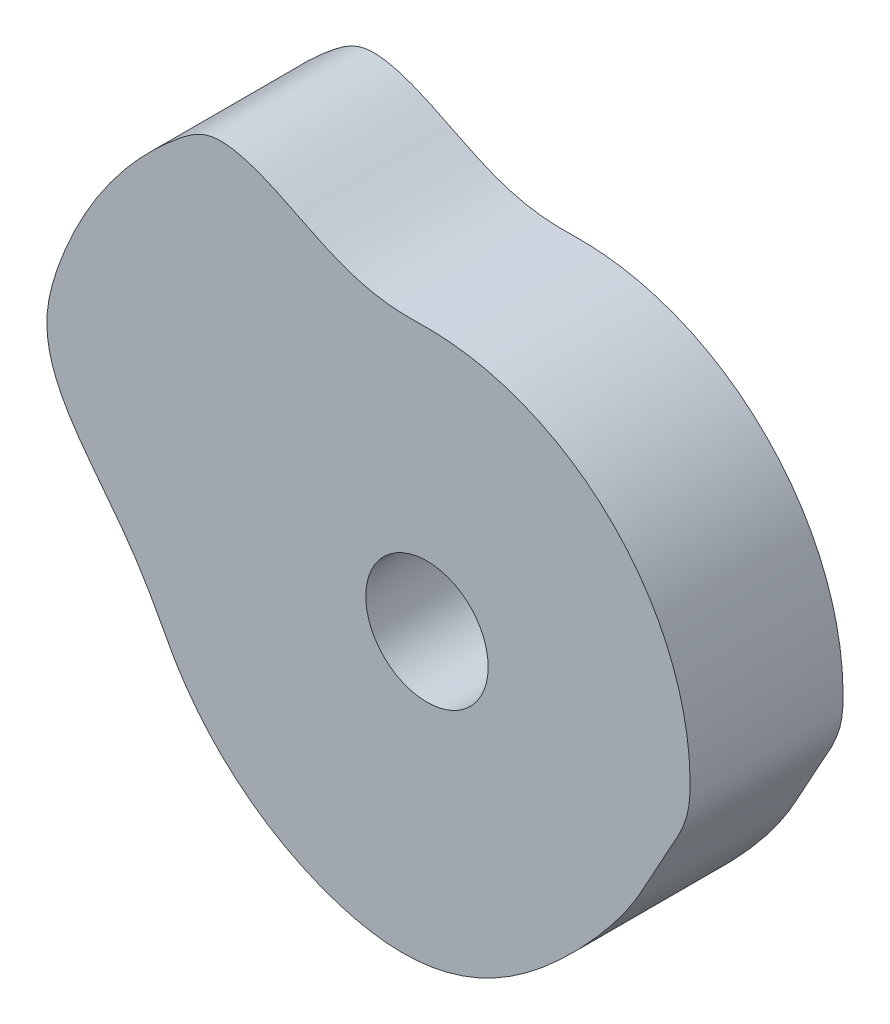
SolidWorks part; units mm, degrees
ref_plane "前视基准面" through (0, 0, 0) normal (0, 0, 1) x (1, 0, 0)
ref_plane "上视基准面" through (0, 0, 0) normal (0, 1, 0) x (1, 0, 0)
ref_plane "右视基准面" through (0, 0, 0) normal (1, 0, 0) x (0, 0, -1)
other "Configuration Table"
curve "曲线1"
sketch "草图1" plane through (0, 0, 0) normal (0, 0, 1) x (1, 0, 0)
  spline S0 degree 3 poles (0.3723, 42.999) (-0.0088, 43.0005) (-0.4074, 42.9988) (-0.8321, 42.9946) (-1.2941, 42.9895) (-1.7902, 42.9845) (-2.3194, 42.9823) (-2.8809, 42.9844) (-3.4733, 42.9934) (-4.0947, 43.0117) (-4.7431, 43.0421) (-5.4158, 43.0865) (-6.1099, 43.1475) (-6.822, 43.2268) (-7.5486, 43.3262) (-8.2858, 43.4462) (-9.0301, 43.5878) (-9.7777, 43.7508) (-10.5255, 43.9345) (-11.2705, 44.138) (-12.0104, 44.3601) (-12.7432, 44.5992) (-13.4676, 44.8538) (-14.1826, 45.1216) (-14.8878, 45.4014) (-15.5832, 45.6911) (-16.2688, 45.989) (-16.9451, 46.2936) (-17.6126, 46.6034) (-18.2719, 46.917) (-18.9237, 47.2326) (-19.5683, 47.5495) (-20.2066, 47.8659) (-20.8388, 48.1807) (-21.4653, 48.4929) (-22.0864, 48.8008) (-22.7021, 49.1035) (-23.3123, 49.3998) (-23.9171, 49.6882) (-24.5158, 49.9681) (-25.1084, 50.2376) (-25.6941, 50.4963) (-26.2722, 50.7427) (-26.8421, 50.9761) (-27.4028, 51.1954) (-27.9536, 51.3998) (-28.4933, 51.5888) (-29.0211, 51.7618) (-29.5359, 51.9181) (-30.0368, 52.0575) (-30.5227, 52.1801) (-30.9929, 52.2857) (-31.4466, 52.3748) (-31.8832, 52.4473) (-32.3023, 52.504) (-32.7036, 52.5455) (-33.0873, 52.5725) (-33.4537, 52.5858) (-33.8034, 52.5862) (-34.1374, 52.5746) (-34.4569, 52.5518) (-34.7635, 52.5182) (-35.0591, 52.4744) (-35.3455, 52.4209) (-35.6251, 52.3571) (-35.9, 52.2834) (-36.1727, 52.199) (-36.4454, 52.1033) (-36.7201, 51.9955) (-36.9992, 51.8744) (-37.2841, 51.7388) (-37.5767, 51.5877) (-37.8784, 51.4199) (-38.1902, 51.234) (-38.5133, 51.0294) (-38.8483, 50.8049) (-39.196, 50.5601) (-39.5571, 50.2945) (-39.932, 50.0077) (-40.3214, 49.6999) (-40.7256, 49.3712) (-41.1422, 49.0247) (-41.5653, 48.6666) (-41.9883, 48.302) (-42.4083, 47.9338) (-42.825, 47.5619) (-43.2383, 47.1863) (-43.6484, 46.8072) (-44.0553, 46.4246) (-44.4586, 46.0382) (-44.8588, 45.6486) (-45.2553, 45.2553) (-45.6486, 44.8588) (-46.0382, 44.4586) (-46.4246, 44.0553) (-46.8072, 43.6484) (-47.1863, 43.2383) (-47.5619, 42.825) (-47.9338, 42.4083) (-48.302, 41.9883) (-48.6666, 41.5653) (-49.0274, 41.1389) (-49.3846, 40.7096) (-49.7379, 40.277) (-50.0875, 39.8414) (-50.4334, 39.4028) (-50.7752, 38.9612) (-51.1134, 38.5167) (-51.4474, 38.0691) (-51.7778, 37.6188) (-52.1041, 37.1655) (-52.4264, 36.7093) (-52.7448, 36.2505) (-53.059, 35.7887) (-53.3694, 35.3245) (-53.6755, 34.8573) (-53.9778, 34.3877) (-54.2757, 33.9152) (-54.5697, 33.4403) (-54.8593, 32.9628) (-55.1451, 32.4829) (-55.4263, 32.0004) (-55.7035, 31.5155) (-55.9764, 31.0282) (-56.245, 30.5386) (-56.5093, 30.0465) (-56.7694, 29.5523) (-57.0251, 29.0558) (-57.2765, 28.5571) (-57.5235, 28.0561) (-57.7662, 27.5531) (-58.0044, 27.0479) (-58.2382, 26.5407) (-58.4676, 26.0315) (-58.6925, 25.5202) (-58.9131, 25.0071) (-59.129, 24.492) (-59.3406, 23.9751) (-59.5475, 23.4564) (-59.7498, 22.9358) (-59.9478, 22.4136) (-60.1405, 21.8911) (-60.3271, 21.3716) (-60.5058, 20.858) (-60.6762, 20.3517) (-60.8374, 19.8525) (-60.9898, 19.3605) (-61.1329, 18.8754) (-61.2662, 18.397) (-61.3902, 17.9252) (-61.5043, 17.4599) (-61.6087, 17.0007) (-61.7032, 16.5475) (-61.7878, 16.1) (-61.8625, 15.6578) (-61.9274, 15.2207) (-61.9825, 14.7884) (-62.0278, 14.3604) (-62.0633, 13.9363) (-62.0889, 13.5158) (-62.1049, 13.0983) (-62.1111, 12.6835) (-62.1077, 12.2709) (-62.0944, 11.8599) (-62.0712, 11.4501) (-62.0383, 11.0411) (-61.9954, 10.6324) (-61.9424, 10.2236) (-61.8794, 9.8142) (-61.806, 9.4039) (-61.7222, 8.9924) (-61.628, 8.5793) (-61.523, 8.1644) (-61.4072, 7.7475) (-61.2805, 7.3282) (-61.1427, 6.9067) (-60.9939, 6.4827) (-60.8339, 6.0561) (-60.6626, 5.6271) (-60.4802, 5.1954) (-60.2866, 4.7613) (-60.0819, 4.3247) (-59.8663, 3.8857) (-59.6397, 3.4445) (-59.4024, 3.0011) (-59.1546, 2.5557) (-58.8966, 2.1083) (-58.6286, 1.6591) (-58.351, 1.2081) (-58.064, 0.7555) (-57.7682, 0.3012) (-57.4636, -0.1543) (-57.151, -0.6115) (-56.8307, -1.0702) (-56.503, -1.5301) (-56.1686, -1.9917) (-55.8277, -2.4547) (-55.4811, -2.9192) (-55.1289, -3.3854) (-54.7721, -3.8533) (-54.4107, -4.3231) (-54.0456, -4.7949) (-53.6771, -5.2688) (-53.3058, -5.745) (-52.9324, -6.2237) (-52.5569, -6.7049) (-52.1807, -7.189) (-51.8034, -7.6757) (-51.4264, -8.1657) (-51.0497, -8.6586) (-50.6741, -9.1547) (-50.3, -9.6538) (-49.9282, -10.1561) (-49.5592, -10.6614) (-49.1932, -11.1694) (-48.8315, -11.6802) (-48.4738, -12.1931) (-48.1211, -12.7082) (-47.7739, -13.2248) (-47.4323, -13.7423) (-47.0968, -14.2603) (-46.7682, -14.7783) (-46.4461, -15.2954) (-46.1309, -15.811) (-45.8231, -16.3243) (-45.5225, -16.8346) (-45.2291, -17.3411) (-44.9431, -17.8429) (-44.664, -18.3393) (-44.3922, -18.8296) (-44.1269, -19.3128) (-43.8685, -19.7886) (-43.616, -20.2559) (-43.3698, -20.7143) (-43.1287, -21.163) (-42.8934, -21.6019) (-42.6626, -22.0299) (-42.4367, -22.4469) (-42.2149, -22.8524) (-41.997, -23.246) (-41.7828, -23.6276) (-41.5708, -23.9985) (-41.3587, -24.3621) (-41.1445, -24.7221) (-40.9272, -25.0802) (-40.7068, -25.4364) (-40.4833, -25.7907) (-40.2567, -26.143) (-40.027, -26.4933) (-39.7943, -26.8416) (-39.5586, -27.1879) (-39.3198, -27.532) (-39.0779, -27.874) (-38.8333, -28.2141) (-38.5856, -28.5518) (-38.335, -28.8875) (-38.0815, -29.2209) (-37.825, -29.5521) (-37.5657, -29.8811) (-37.3035, -30.2078) (-37.0385, -30.5322) (-36.7705, -30.8542) (-36.5, -31.1739) (-36.2265, -31.4912) (-35.9504, -31.8062) (-35.6715, -32.1187) (-35.3897, -32.4287) (-35.1055, -32.7363) (-34.8184, -33.0414) (-34.5288, -33.344) (-34.2364, -33.644) (-33.9415, -33.9415) (-33.644, -34.2364) (-33.344, -34.5288) (-33.0414, -34.8184) (-32.7363, -35.1055) (-32.4287, -35.3897) (-32.1187, -35.6715) (-31.8062, -35.9504) (-31.4912, -36.2265) (-31.1739, -36.5) (-30.8542, -36.7705) (-30.5322, -37.0385) (-30.2078, -37.3035) (-29.8811, -37.5657) (-29.5521, -37.825) (-29.2209, -38.0815) (-28.8875, -38.335) (-28.5518, -38.5856) (-28.2141, -38.8333) (-27.874, -39.0779) (-27.532, -39.3198) (-27.1879, -39.5586) (-26.8416, -39.7943) (-26.4933, -40.027) (-26.143, -40.2567) (-25.7907, -40.4833) (-25.4364, -40.7068) (-25.0802, -40.9272) (-24.7221, -41.1445) (-24.3621, -41.3587) (-24.0003, -41.5697) (-23.6367, -41.7776) (-23.2711, -41.9823) (-22.9039, -42.1837) (-22.5349, -42.382) (-22.1642, -42.577) (-21.7918, -42.7688) (-21.4177, -42.9573) (-21.0421, -43.1427) (-20.6648, -43.3246) (-20.286, -43.5034) (-19.9055, -43.6786) (-19.5237, -43.8508) (-19.1402, -44.0195) (-18.7553, -44.1847) (-18.369, -44.3468) (-17.9813, -44.5054) (-17.5923, -44.6606) (-17.2019, -44.8125) (-16.8102, -44.9609) (-16.4174, -45.1057) (-16.0242, -45.2469) (-15.6308, -45.3842) (-15.2377, -45.5174) (-14.8448, -45.6467) (-14.4522, -45.7717) (-14.0598, -45.8925) (-13.6678, -46.0093) (-13.276, -46.1215) (-12.8845, -46.2297) (-12.4934, -46.3334) (-12.1026, -46.433) (-11.7122, -46.528) (-11.3222, -46.6186) (-10.9326, -46.7048) (-10.5434, -46.7865) (-10.1546, -46.8637) (-9.7664, -46.9365) (-9.3785, -47.0045) (-8.9912, -47.0682) (-8.6044, -47.127) (-8.2181, -47.1815) (-7.8323, -47.2312) (-7.447, -47.2763) (-7.0623, -47.3167) (-6.6782, -47.3525) (-6.2947, -47.3837) (-5.9118, -47.4101) (-5.5296, -47.4317) (-5.1479, -47.4488) (-4.767, -47.4609) (-4.3866, -47.4686) (-4.007, -47.4714) (-3.628, -47.4695) (-3.2497, -47.4627) (-2.8721, -47.4515) (-2.4953, -47.4354) (-2.1192, -47.4145) (-1.7439, -47.389) (-1.3693, -47.3587) (-0.9954, -47.3237) (-0.6224, -47.284) (-0.2502, -47.2396) (0.1213, -47.1905) (0.4919, -47.1367) (0.8617, -47.0782) (1.2306, -47.015) (1.5987, -46.9471) (1.9659, -46.8748) (2.3322, -46.7976) (2.6976, -46.7161) (3.0621, -46.6297) (3.4258, -46.539) (3.7884, -46.4435) (4.1501, -46.3436) (4.5108, -46.2392) (4.8706, -46.1303) (5.2294, -46.0168) (5.5872, -45.8991) (5.9439, -45.7769) (6.2995, -45.6502) (6.6542, -45.5195) (7.0077, -45.384) (7.3602, -45.2448) (7.7116, -45.1009) (8.0619, -44.9531) (8.411, -44.8009) (8.759, -44.6447) (9.1058, -44.4845) (9.4515, -44.3202) (9.796, -44.152) (10.1393, -43.9798) (10.4813, -43.8036) (10.8222, -43.6238) (11.1618, -43.44) (11.5002, -43.2526) (11.8374, -43.0616) (12.1733, -42.8668) (12.5079, -42.6685) (12.8413, -42.4668) (13.1732, -42.2614) (13.504, -42.0529) (13.8335, -41.841) (14.1616, -41.6257) (14.4885, -41.4074) (14.814, -41.1857) (15.1383, -40.9611) (15.4612, -40.7335) (15.7827, -40.5029) (16.103, -40.2695) (16.4219, -40.0332) (16.7395, -39.7942) (17.0559, -39.5526) (17.3707, -39.3082) (17.6843, -39.0615) (17.9966, -38.8121) (18.3076, -38.5604) (18.6173, -38.3064) (18.9256, -38.0501) (19.2325, -37.7915) (19.5381, -37.5309) (19.8424, -37.2682) (20.1453, -37.0034) (20.447, -36.7368) (20.7472, -36.4682) (21.0461, -36.1979) (21.3436, -35.9258) (21.6399, -35.6521) (21.9346, -35.3767) (22.228, -35.0998) (22.52, -34.8214) (22.8106, -34.5416) (23.0998, -34.2605) (23.3875, -33.9779) (23.6738, -33.6943) (23.9586, -33.4094) (24.2419, -33.1233) (24.5236, -32.8361) (24.8039, -32.5479) (25.0825, -32.2587) (25.3596, -31.9687) (25.635, -31.6777) (25.9088, -31.3859) (26.1809, -31.0934) (26.4511, -30.7999) (26.7198, -30.506) (26.9865, -30.2113) (27.2516, -29.916) (27.5145, -29.6201) (27.7757, -29.3237) (28.0348, -29.0268) (28.2919, -28.7293) (28.547, -28.4315) (28.7999, -28.1333) (29.0507, -27.8346) (29.2993, -27.5356) (29.5456, -27.2363) (29.7896, -26.9367) (30.0312, -26.6368) (30.2706, -26.3367) (30.5071, -26.0361) (30.7415, -25.7356) (30.9731, -25.4348) (31.2021, -25.1337) (31.4284, -24.8325) (31.652, -24.5312) (31.8728, -24.2298) (32.0907, -23.9282) (32.3057, -23.6265) (32.5178, -23.3246) (32.7268, -23.0227) (32.9328, -22.7207) (33.1358, -22.4187) (33.3354, -22.1165) (33.532, -21.8144) (33.7253, -21.5122) (33.9152, -21.2099) (34.1018, -20.9076) (34.2851, -20.6054) (34.4648, -20.303) (34.6424, -19.9987) (34.8198, -19.6881) (34.9999, -19.3674) (35.184, -19.0349) (35.3721, -18.691) (35.5643, -18.3364) (35.7607, -17.9716) (35.9613, -17.5975) (36.1661, -17.215) (36.3749, -16.825) (36.5877, -16.4287) (36.8042, -16.027) (37.0241, -15.6211) (37.2468, -15.2121) (37.4723, -14.8014) (37.6995, -14.3898) (37.9284, -13.9787) (38.1577, -13.5688) (38.3874, -13.1614) (38.6162, -12.7573) (38.8434, -12.3573) (39.0685, -11.9622) (39.2907, -11.5727) (39.509, -11.1893) (39.7228, -10.8125) (39.9315, -10.4427) (40.1344, -10.0803) (40.3308, -9.7255) (40.5204, -9.3786) (40.7028, -9.0395) (40.8774, -8.7083) (41.0443, -8.3852) (41.2027, -8.0698) (41.353, -7.7621) (41.4952, -7.4621) (41.6289, -7.1691) (41.7546, -6.8829) (41.8723, -6.6032) (41.9821, -6.3292) (42.0847, -6.0606) (42.1801, -5.7965) (42.2686, -5.5361) (42.3508, -5.2787) (42.4267, -5.0231) (42.497, -4.7686) (42.5619, -4.5139) (42.6214, -4.2581) (42.6762, -4) (42.7263, -3.7385) (42.7718, -3.4725) (42.813, -3.201) (42.8499, -2.9229) (42.8826, -2.6373) (42.9111, -2.3433) (42.9358, -2.0401) (42.9562, -1.727) (42.9726, -1.4034) (42.9851, -1.0688) (42.994, -0.7229) (42.9989, -0.3653) (43.0005, 0.002) (42.9989, 0.3752) (42.994, 0.7505) (42.9859, 1.1256) (42.9743, 1.5007) (42.9597, 1.8756) (42.9417, 2.2505) (42.9203, 2.6251) (42.8959, 2.9996) (42.8679, 3.3738) (42.837, 3.7478) (42.8025, 4.1214) (42.7649, 4.4948) (42.7241, 4.8678) (42.6801, 5.2404) (42.6326, 5.6127) (42.582, 5.9845) (42.5283, 6.3559) (42.4711, 6.7268) (42.4109, 7.0971) (42.3472, 7.4669) (42.2806, 7.8362) (42.2105, 8.2049) (42.1374, 8.5729) (42.0608, 8.9403) (41.9812, 9.307) (41.8984, 9.673) (41.8125, 10.0383) (41.7232, 10.4028) (41.6308, 10.7664) (41.5353, 11.1294) (41.4366, 11.4914) (41.3349, 11.8526) (41.2297, 12.2128) (41.1217, 12.5722) (41.0103, 12.9305) (40.8959, 13.2879) (40.7784, 13.6443) (40.6578, 13.9996) (40.5341, 14.3539) (40.4073, 14.7071) (40.2774, 15.0591) (40.1445, 15.41) (40.0085, 15.7598) (39.8694, 16.1083) (39.7273, 16.4556) (39.5822, 16.8016) (39.4341, 17.1464) (39.283, 17.4899) (39.1288, 17.832) (38.9717, 18.1728) (38.8117, 18.5123) (38.6486, 18.8502) (38.4827, 19.1868) (38.3138, 19.5218) (38.142, 19.8555) (37.9672, 20.1875) (37.7896, 20.5181) (37.6091, 20.847) (37.4258, 21.1745) (37.2396, 21.5002) (37.0506, 21.8244) (36.8587, 22.1469) (36.6639, 22.4677) (36.4666, 22.7868) (36.2663, 23.1042) (36.0633, 23.4198) (35.8576, 23.7336) (35.649, 24.0456) (35.4379, 24.3558) (35.2239, 24.6641) (35.0074, 24.9706) (34.7882, 25.2751) (34.5663, 25.5777) (34.3417, 25.8783) (34.1146, 26.177) (33.8849, 26.4737) (33.6526, 26.7685) (33.4177, 27.0611) (33.1803, 27.3518) (32.9403, 27.6402) (32.698, 27.9267) (32.4528, 28.2108) (32.2056, 28.4931) (31.9556, 28.7729) (31.7033, 29.0508) (31.4486, 29.3263) (31.1915, 29.5996) (30.932, 29.8707) (30.6702, 30.1395) (30.406, 30.406) (30.1395, 30.6702) (29.8707, 30.932) (29.5996, 31.1915) (29.3263, 31.4486) (29.0508, 31.7033) (28.7729, 31.9556) (28.4931, 32.2056) (28.2108, 32.4528) (27.9267, 32.698) (27.6402, 32.9403) (27.3518, 33.1803) (27.0611, 33.4177) (26.7685, 33.6526) (26.4737, 33.8849) (26.177, 34.1146) (25.8783, 34.3417) (25.5777, 34.5663) (25.2751, 34.7882) (24.9706, 35.0074) (24.6641, 35.2239) (24.3558, 35.4379) (24.0456, 35.649) (23.7336, 35.8576) (23.4198, 36.0633) (23.1042, 36.2663) (22.7868, 36.4666) (22.4677, 36.6639) (22.1469, 36.8587) (21.8244, 37.0506) (21.5002, 37.2396) (21.1745, 37.4258) (20.847, 37.6091) (20.5181, 37.7896) (20.1875, 37.9672) (19.8555, 38.142) (19.5218, 38.3138) (19.1868, 38.4827) (18.8502, 38.6486) (18.5123, 38.8117) (18.1728, 38.9717) (17.832, 39.1288) (17.4899, 39.283) (17.1464, 39.4341) (16.8016, 39.5822) (16.4556, 39.7273) (16.1083, 39.8694) (15.7598, 40.0085) (15.41, 40.1445) (15.0591, 40.2774) (14.7071, 40.4073) (14.3539, 40.5341) (13.9996, 40.6578) (13.6443, 40.7784) (13.2879, 40.8959) (12.9305, 41.0103) (12.5722, 41.1217) (12.2128, 41.2297) (11.8526, 41.3349) (11.4914, 41.4366) (11.1294, 41.5353) (10.7664, 41.6308) (10.4028, 41.7232) (10.0383, 41.8125) (9.673, 41.8984) (9.307, 41.9812) (8.9403, 42.0608) (8.5729, 42.1374) (8.2049, 42.2105) (7.8362, 42.2806) (7.4669, 42.3472) (7.0971, 42.4109) (6.7268, 42.4711) (6.3559, 42.5283) (5.9845, 42.582) (5.6127, 42.6326) (5.2404, 42.6801) (4.8678, 42.7241) (4.4948, 42.7649) (4.1214, 42.8025) (3.7478, 42.837) (3.3738, 42.8679) (2.9996, 42.8959) (2.6251, 42.9203) (2.2505, 42.9417) (1.8756, 42.9597) (1.5007, 42.9743) (1.1256, 42.9859) (0.7505, 42.994) (0.3723, 42.999) (-0.0088, 43.0005) (-0.4074, 42.9988) knots -0.003606 -0.002413 -0.00122 0 0.001222 0.002581 0.00405 0.005628 0.007311 0.009098 0.010982 0.012961 0.015026 0.017172 0.01939 0.02167 0.024004 0.026382 0.028793 0.031228 0.033678 0.036135 0.038593 0.041044 0.043486 0.045914 0.048326 0.050721 0.053097 0.055455 0.057794 0.060115 0.062417 0.0647 0.066965 0.06921 0.071436 0.07364 0.075821 0.077978 0.080109 0.082211 0.084281 0.086317 0.088316 0.090274 0.092189 0.094058 0.095877 0.097643 0.099354 0.101007 0.1026 0.104133 0.105602 0.107009 0.108353 0.109634 0.110856 0.11202 0.11313 0.11419 0.115206 0.116184 0.117131 0.118055 0.118963 0.119865 0.120769 0.121684 0.122619 0.123583 0.124584 0.125628 0.126724 0.127876 0.129089 0.13037 0.131721 0.133145 0.134645 0.136222 0.137878 0.139613 0.141388 0.143164 0.144939 0.146715 0.14849 0.150265 0.152041 0.153816 0.155592 0.157367 0.159142 0.160918 0.162693 0.164468 0.166244 0.168019 0.169795 0.17157 0.173345 0.175121 0.176896 0.178671 0.180447 0.182222 0.183998 0.185773 0.187548 0.189324 0.191099 0.192874 0.19465 0.196425 0.1982 0.199976 0.201751 0.203527 0.205302 0.207078 0.208853 0.210628 0.212404 0.214179 0.215954 0.21773 0.219505 0.22128 0.223056 0.224831 0.226607 0.228382 0.230157 0.231933 0.233708 0.235483 0.237259 0.239034 0.24081 0.242585 0.24436 0.246136 0.247895 0.249624 0.251322 0.252989 0.254627 0.256234 0.257812 0.259363 0.260885 0.262382 0.263853 0.2653 0.266725 0.268129 0.269514 0.270881 0.272233 0.273571 0.274899 0.276216 0.277527 0.278834 0.280137 0.281441 0.282746 0.284056 0.285372 0.286696 0.28803 0.289376 0.290736 0.292111 0.293503 0.294912 0.29634 0.297788 0.299256 0.300746 0.302257 0.303789 0.305344 0.30692 0.308519 0.310139 0.311781 0.313444 0.315128 0.316831 0.318555 0.320297 0.322058 0.323836 0.325632 0.327443 0.329271 0.331114 0.332971 0.334842 0.336727 0.338623 0.340532 0.342451 0.344382 0.346322 0.348271 0.350229 0.352194 0.354167 0.356145 0.358128 0.360115 0.362105 0.364095 0.366086 0.368074 0.370059 0.372038 0.37401 0.375972 0.377923 0.379861 0.381782 0.383685 0.385569 0.38743 0.389267 0.391077 0.39286 0.394613 0.396335 0.398023 0.399678 0.401297 0.402881 0.404427 0.405934 0.407404 0.408834 0.410225 0.411577 0.412908 0.41424 0.415571 0.416903 0.418234 0.419566 0.420897 0.422229 0.42356 0.424892 0.426223 0.427555 0.428887 0.430218 0.431549 0.432881 0.434213 0.435544 0.436876 0.438207 0.439539 0.44087 0.442202 0.443533 0.444865 0.446196 0.447528 0.44886 0.450191 0.451523 0.452854 0.454186 0.455517 0.456849 0.45818 0.459512 0.460843 0.462175 0.463506 0.464838 0.466169 0.467501 0.468833 0.470164 0.471496 0.472827 0.474159 0.47549 0.476822 0.478153 0.479485 0.480816 0.482148 0.483479 0.484811 0.486143 0.487474 0.488806 0.490137 0.491469 0.4928 0.494132 0.495463 0.496795 0.498126 0.499458 0.500789 0.502121 0.503453 0.504784 0.506115 0.507447 0.508778 0.51011 0.511442 0.512773 0.514105 0.515436 0.516768 0.518099 0.519428 0.520753 0.522072 0.523387 0.524697 0.526001 0.527302 0.528597 0.529888 0.531175 0.532456 0.533734 0.535006 0.536275 0.537539 0.538799 0.540054 0.541306 0.542554 0.543797 0.545038 0.546274 0.547507 0.548737 0.549963 0.551186 0.552406 0.553623 0.554837 0.556049 0.557258 0.558465 0.559669 0.560872 0.562072 0.563271 0.564469 0.565664 0.566859 0.568053 0.569245 0.570436 0.571627 0.572818 0.574008 0.575198 0.576387 0.577577 0.578767 0.579957 0.581148 0.582339 0.583531 0.584724 0.585917 0.587112 0.588308 0.589506 0.590704 0.591904 0.593106 0.594309 0.595514 0.596721 0.597929 0.59914 0.600352 0.601567 0.602783 0.604002 0.605223 0.606446 0.607671 0.608898 0.610128 0.61136 0.612594 0.613831 0.615069 0.61631 0.617553 0.618798 0.620046 0.621295 0.622547 0.623801 0.625057 0.626315 0.627574 0.628836 0.6301 0.631365 0.632632 0.633901 0.635171 0.636443 0.637716 0.63899 0.640266 0.641543 0.642821 0.6441 0.645379 0.64666 0.647941 0.649223 0.650505 0.651787 0.65307 0.654352 0.655635 0.656917 0.658199 0.65948 0.66076 0.66204 0.663319 0.664597 0.665874 0.667149 0.668422 0.669694 0.670965 0.672233 0.673499 0.674762 0.676024 0.677282 0.678538 0.679791 0.68104 0.682287 0.68353 0.68477 0.686006 0.687238 0.688466 0.689691 0.690911 0.692127 0.693338 0.694545 0.695748 0.696945 0.698138 0.699326 0.700509 0.701686 0.702859 0.704026 0.705188 0.706345 0.707496 0.708642 0.709783 0.710917 0.712046 0.71317 0.714288 0.715401 0.71653 0.7177 0.718908 0.720154 0.721437 0.722755 0.724105 0.725486 0.726893 0.728324 0.729776 0.731244 0.732726 0.734217 0.735712 0.73721 0.738704 0.740192 0.741669 0.743133 0.744579 0.746005 0.747409 0.748787 0.750137 0.751458 0.752747 0.754004 0.755229 0.756419 0.757575 0.758697 0.759785 0.76084 0.761863 0.762856 0.76382 0.764757 0.765671 0.766562 0.767435 0.768293 0.769139 0.769977 0.770811 0.771645 0.772482 0.773327 0.774184 0.775056 0.775946 0.776859 0.777797 0.778763 0.779759 0.780789 0.781853 0.782952 0.784089 0.785263 0.786455 0.787648 0.788841 0.790034 0.791227 0.792419 0.793613 0.794805 0.795998 0.797191 0.798384 0.799577 0.800769 0.801962 0.803155 0.804348 0.805541 0.806734 0.807926 0.809119 0.810312 0.811505 0.812698 0.813891 0.815083 0.816276 0.817469 0.818662 0.819855 0.821048 0.822241 0.823433 0.824626 0.825819 0.827012 0.828205 0.829397 0.83059 0.831783 0.832976 0.834169 0.835361 0.836554 0.837747 0.83894 0.840133 0.841326 0.842519 0.843711 0.844904 0.846097 0.84729 0.848483 0.849676 0.850868 0.852061 0.853254 0.854447 0.85564 0.856833 0.858025 0.859218 0.860411 0.861604 0.862797 0.86399 0.865182 0.866375 0.867568 0.868761 0.869954 0.871147 0.872339 0.873532 0.874725 0.875918 0.877111 0.878304 0.879496 0.880689 0.881882 0.883075 0.884268 0.885461 0.886653 0.887846 0.889039 0.890232 0.891425 0.892617 0.89381 0.895003 0.896196 0.897389 0.898582 0.899774 0.900967 0.90216 0.903353 0.904546 0.905739 0.906931 0.908124 0.909317 0.91051 0.911703 0.912895 0.914088 0.915281 0.916474 0.917667 0.91886 0.920053 0.921245 0.922438 0.923631 0.924824 0.926017 0.92721 0.928402 0.929595 0.930788 0.931981 0.933174 0.934367 0.935559 0.936752 0.937945 0.939138 0.940331 0.941524 0.942716 0.943909 0.945102 0.946295 0.947488 0.94868 0.949874 0.951066 0.952259 0.953452 0.954645 0.955838 0.95703 0.958223 0.959416 0.960609 0.961802 0.962994 0.964187 0.96538 0.966573 0.967766 0.968959 0.970152 0.971344 0.972537 0.97373 0.974923 0.976116 0.977309 0.978501 0.979694 0.980887 0.98208 0.983273 0.984466 0.985658 0.986851 0.988044 0.989237 0.99043 0.991622 0.992816 0.994008 0.995201 0.996394 0.997587 0.99878 1 1.001222 1.002581 1.00405 only from (-0.0087, 43) to (-0.0087, 43) construction
  spline S1 degree 3 poles (0.3723, 42.999) (-0.0088, 43.0005) (-0.4074, 42.9988) (-0.8321, 42.9946) (-1.2941, 42.9895) (-1.7902, 42.9845) (-2.3194, 42.9823) (-2.8809, 42.9844) (-3.4733, 42.9934) (-4.0947, 43.0117) (-4.7431, 43.0421) (-5.4158, 43.0865) (-6.1099, 43.1475) (-6.822, 43.2268) (-7.5486, 43.3262) (-8.2858, 43.4462) (-9.0301, 43.5878) (-9.7777, 43.7508) (-10.5255, 43.9345) (-11.2705, 44.138) (-12.0104, 44.3601) (-12.7432, 44.5992) (-13.4676, 44.8538) (-14.1826, 45.1216) (-14.8878, 45.4014) (-15.5832, 45.6911) (-16.2688, 45.989) (-16.9451, 46.2936) (-17.6126, 46.6034) (-18.2719, 46.917) (-18.9237, 47.2326) (-19.5683, 47.5495) (-20.2066, 47.8659) (-20.8388, 48.1807) (-21.4653, 48.4929) (-22.0864, 48.8008) (-22.7021, 49.1035) (-23.3123, 49.3998) (-23.9171, 49.6882) (-24.5158, 49.9681) (-25.1084, 50.2376) (-25.6941, 50.4963) (-26.2722, 50.7427) (-26.8421, 50.9761) (-27.4028, 51.1954) (-27.9536, 51.3998) (-28.4933, 51.5888) (-29.0211, 51.7618) (-29.5359, 51.9181) (-30.0368, 52.0575) (-30.5227, 52.1801) (-30.9929, 52.2857) (-31.4466, 52.3748) (-31.8832, 52.4473) (-32.3023, 52.504) (-32.7036, 52.5455) (-33.0873, 52.5725) (-33.4537, 52.5858) (-33.8034, 52.5862) (-34.1374, 52.5746) (-34.4569, 52.5518) (-34.7635, 52.5182) (-35.0591, 52.4744) (-35.3455, 52.4209) (-35.6251, 52.3571) (-35.9, 52.2834) (-36.1727, 52.199) (-36.4454, 52.1033) (-36.7201, 51.9955) (-36.9992, 51.8744) (-37.2841, 51.7388) (-37.5767, 51.5877) (-37.8784, 51.4199) (-38.1902, 51.234) (-38.5133, 51.0294) (-38.8483, 50.8049) (-39.196, 50.5601) (-39.5571, 50.2945) (-39.932, 50.0077) (-40.3214, 49.6999) (-40.7256, 49.3712) (-41.1422, 49.0247) (-41.5653, 48.6666) (-41.9883, 48.302) (-42.4083, 47.9338) (-42.825, 47.5619) (-43.2383, 47.1863) (-43.6484, 46.8072) (-44.0553, 46.4246) (-44.4586, 46.0382) (-44.8588, 45.6486) (-45.2553, 45.2553) (-45.6486, 44.8588) (-46.0382, 44.4586) (-46.4246, 44.0553) (-46.8072, 43.6484) (-47.1863, 43.2383) (-47.5619, 42.825) (-47.9338, 42.4083) (-48.302, 41.9883) (-48.6666, 41.5653) (-49.0274, 41.1389) (-49.3846, 40.7096) (-49.7379, 40.277) (-50.0875, 39.8414) (-50.4334, 39.4028) (-50.7752, 38.9612) (-51.1134, 38.5167) (-51.4474, 38.0691) (-51.7778, 37.6188) (-52.1041, 37.1655) (-52.4264, 36.7093) (-52.7448, 36.2505) (-53.059, 35.7887) (-53.3694, 35.3245) (-53.6755, 34.8573) (-53.9778, 34.3877) (-54.2757, 33.9152) (-54.5697, 33.4403) (-54.8593, 32.9628) (-55.1451, 32.4829) (-55.4263, 32.0004) (-55.7035, 31.5155) (-55.9764, 31.0282) (-56.245, 30.5386) (-56.5093, 30.0465) (-56.7694, 29.5523) (-57.0251, 29.0558) (-57.2765, 28.5571) (-57.5235, 28.0561) (-57.7662, 27.5531) (-58.0044, 27.0479) (-58.2382, 26.5407) (-58.4676, 26.0315) (-58.6925, 25.5202) (-58.9131, 25.0071) (-59.129, 24.492) (-59.3406, 23.9751) (-59.5475, 23.4564) (-59.7498, 22.9358) (-59.9478, 22.4136) (-60.1405, 21.8911) (-60.3271, 21.3716) (-60.5058, 20.858) (-60.6762, 20.3517) (-60.8374, 19.8525) (-60.9898, 19.3605) (-61.1329, 18.8754) (-61.2662, 18.397) (-61.3902, 17.9252) (-61.5043, 17.4599) (-61.6087, 17.0007) (-61.7032, 16.5475) (-61.7878, 16.1) (-61.8625, 15.6578) (-61.9274, 15.2207) (-61.9825, 14.7884) (-62.0278, 14.3604) (-62.0633, 13.9363) (-62.0889, 13.5158) (-62.1049, 13.0983) (-62.1111, 12.6835) (-62.1077, 12.2709) (-62.0944, 11.8599) (-62.0712, 11.4501) (-62.0383, 11.0411) (-61.9954, 10.6324) (-61.9424, 10.2236) (-61.8794, 9.8142) (-61.806, 9.4039) (-61.7222, 8.9924) (-61.628, 8.5793) (-61.523, 8.1644) (-61.4072, 7.7475) (-61.2805, 7.3282) (-61.1427, 6.9067) (-60.9939, 6.4827) (-60.8339, 6.0561) (-60.6626, 5.6271) (-60.4802, 5.1954) (-60.2866, 4.7613) (-60.0819, 4.3247) (-59.8663, 3.8857) (-59.6397, 3.4445) (-59.4024, 3.0011) (-59.1546, 2.5557) (-58.8966, 2.1083) (-58.6286, 1.6591) (-58.351, 1.2081) (-58.064, 0.7555) (-57.7682, 0.3012) (-57.4636, -0.1543) (-57.151, -0.6115) (-56.8307, -1.0702) (-56.503, -1.5301) (-56.1686, -1.9917) (-55.8277, -2.4547) (-55.4811, -2.9192) (-55.1289, -3.3854) (-54.7721, -3.8533) (-54.4107, -4.3231) (-54.0456, -4.7949) (-53.6771, -5.2688) (-53.3058, -5.745) (-52.9324, -6.2237) (-52.5569, -6.7049) (-52.1807, -7.189) (-51.8034, -7.6757) (-51.4264, -8.1657) (-51.0497, -8.6586) (-50.6741, -9.1547) (-50.3, -9.6538) (-49.9282, -10.1561) (-49.5592, -10.6614) (-49.1932, -11.1694) (-48.8315, -11.6802) (-48.4738, -12.1931) (-48.1211, -12.7082) (-47.7739, -13.2248) (-47.4323, -13.7423) (-47.0968, -14.2603) (-46.7682, -14.7783) (-46.4461, -15.2954) (-46.1309, -15.811) (-45.8231, -16.3243) (-45.5225, -16.8346) (-45.2291, -17.3411) (-44.9431, -17.8429) (-44.664, -18.3393) (-44.3922, -18.8296) (-44.1269, -19.3128) (-43.8685, -19.7886) (-43.616, -20.2559) (-43.3698, -20.7143) (-43.1287, -21.163) (-42.8934, -21.6019) (-42.6626, -22.0299) (-42.4367, -22.4469) (-42.2149, -22.8524) (-41.997, -23.246) (-41.7828, -23.6276) (-41.5708, -23.9985) (-41.3587, -24.3621) (-41.1445, -24.7221) (-40.9272, -25.0802) (-40.7068, -25.4364) (-40.4833, -25.7907) (-40.2567, -26.143) (-40.027, -26.4933) (-39.7943, -26.8416) (-39.5586, -27.1879) (-39.3198, -27.532) (-39.0779, -27.874) (-38.8333, -28.2141) (-38.5856, -28.5518) (-38.335, -28.8875) (-38.0815, -29.2209) (-37.825, -29.5521) (-37.5657, -29.8811) (-37.3035, -30.2078) (-37.0385, -30.5322) (-36.7705, -30.8542) (-36.5, -31.1739) (-36.2265, -31.4912) (-35.9504, -31.8062) (-35.6715, -32.1187) (-35.3897, -32.4287) (-35.1055, -32.7363) (-34.8184, -33.0414) (-34.5288, -33.344) (-34.2364, -33.644) (-33.9415, -33.9415) (-33.644, -34.2364) (-33.344, -34.5288) (-33.0414, -34.8184) (-32.7363, -35.1055) (-32.4287, -35.3897) (-32.1187, -35.6715) (-31.8062, -35.9504) (-31.4912, -36.2265) (-31.1739, -36.5) (-30.8542, -36.7705) (-30.5322, -37.0385) (-30.2078, -37.3035) (-29.8811, -37.5657) (-29.5521, -37.825) (-29.2209, -38.0815) (-28.8875, -38.335) (-28.5518, -38.5856) (-28.2141, -38.8333) (-27.874, -39.0779) (-27.532, -39.3198) (-27.1879, -39.5586) (-26.8416, -39.7943) (-26.4933, -40.027) (-26.143, -40.2567) (-25.7907, -40.4833) (-25.4364, -40.7068) (-25.0802, -40.9272) (-24.7221, -41.1445) (-24.3621, -41.3587) (-24.0003, -41.5697) (-23.6367, -41.7776) (-23.2711, -41.9823) (-22.9039, -42.1837) (-22.5349, -42.382) (-22.1642, -42.577) (-21.7918, -42.7688) (-21.4177, -42.9573) (-21.0421, -43.1427) (-20.6648, -43.3246) (-20.286, -43.5034) (-19.9055, -43.6786) (-19.5237, -43.8508) (-19.1402, -44.0195) (-18.7553, -44.1847) (-18.369, -44.3468) (-17.9813, -44.5054) (-17.5923, -44.6606) (-17.2019, -44.8125) (-16.8102, -44.9609) (-16.4174, -45.1057) (-16.0242, -45.2469) (-15.6308, -45.3842) (-15.2377, -45.5174) (-14.8448, -45.6467) (-14.4522, -45.7717) (-14.0598, -45.8925) (-13.6678, -46.0093) (-13.276, -46.1215) (-12.8845, -46.2297) (-12.4934, -46.3334) (-12.1026, -46.433) (-11.7122, -46.528) (-11.3222, -46.6186) (-10.9326, -46.7048) (-10.5434, -46.7865) (-10.1546, -46.8637) (-9.7664, -46.9365) (-9.3785, -47.0045) (-8.9912, -47.0682) (-8.6044, -47.127) (-8.2181, -47.1815) (-7.8323, -47.2312) (-7.447, -47.2763) (-7.0623, -47.3167) (-6.6782, -47.3525) (-6.2947, -47.3837) (-5.9118, -47.4101) (-5.5296, -47.4317) (-5.1479, -47.4488) (-4.767, -47.4609) (-4.3866, -47.4686) (-4.007, -47.4714) (-3.628, -47.4695) (-3.2497, -47.4627) (-2.8721, -47.4515) (-2.4953, -47.4354) (-2.1192, -47.4145) (-1.7439, -47.389) (-1.3693, -47.3587) (-0.9954, -47.3237) (-0.6224, -47.284) (-0.2502, -47.2396) (0.1213, -47.1905) (0.4919, -47.1367) (0.8617, -47.0782) (1.2306, -47.015) (1.5987, -46.9471) (1.9659, -46.8748) (2.3322, -46.7976) (2.6976, -46.7161) (3.0621, -46.6297) (3.4258, -46.539) (3.7884, -46.4435) (4.1501, -46.3436) (4.5108, -46.2392) (4.8706, -46.1303) (5.2294, -46.0168) (5.5872, -45.8991) (5.9439, -45.7769) (6.2995, -45.6502) (6.6542, -45.5195) (7.0077, -45.384) (7.3602, -45.2448) (7.7116, -45.1009) (8.0619, -44.9531) (8.411, -44.8009) (8.759, -44.6447) (9.1058, -44.4845) (9.4515, -44.3202) (9.796, -44.152) (10.1393, -43.9798) (10.4813, -43.8036) (10.8222, -43.6238) (11.1618, -43.44) (11.5002, -43.2526) (11.8374, -43.0616) (12.1733, -42.8668) (12.5079, -42.6685) (12.8413, -42.4668) (13.1732, -42.2614) (13.504, -42.0529) (13.8335, -41.841) (14.1616, -41.6257) (14.4885, -41.4074) (14.814, -41.1857) (15.1383, -40.9611) (15.4612, -40.7335) (15.7827, -40.5029) (16.103, -40.2695) (16.4219, -40.0332) (16.7395, -39.7942) (17.0559, -39.5526) (17.3707, -39.3082) (17.6843, -39.0615) (17.9966, -38.8121) (18.3076, -38.5604) (18.6173, -38.3064) (18.9256, -38.0501) (19.2325, -37.7915) (19.5381, -37.5309) (19.8424, -37.2682) (20.1453, -37.0034) (20.447, -36.7368) (20.7472, -36.4682) (21.0461, -36.1979) (21.3436, -35.9258) (21.6399, -35.6521) (21.9346, -35.3767) (22.228, -35.0998) (22.52, -34.8214) (22.8106, -34.5416) (23.0998, -34.2605) (23.3875, -33.9779) (23.6738, -33.6943) (23.9586, -33.4094) (24.2419, -33.1233) (24.5236, -32.8361) (24.8039, -32.5479) (25.0825, -32.2587) (25.3596, -31.9687) (25.635, -31.6777) (25.9088, -31.3859) (26.1809, -31.0934) (26.4511, -30.7999) (26.7198, -30.506) (26.9865, -30.2113) (27.2516, -29.916) (27.5145, -29.6201) (27.7757, -29.3237) (28.0348, -29.0268) (28.2919, -28.7293) (28.547, -28.4315) (28.7999, -28.1333) (29.0507, -27.8346) (29.2993, -27.5356) (29.5456, -27.2363) (29.7896, -26.9367) (30.0312, -26.6368) (30.2706, -26.3367) (30.5071, -26.0361) (30.7415, -25.7356) (30.9731, -25.4348) (31.2021, -25.1337) (31.4284, -24.8325) (31.652, -24.5312) (31.8728, -24.2298) (32.0907, -23.9282) (32.3057, -23.6265) (32.5178, -23.3246) (32.7268, -23.0227) (32.9328, -22.7207) (33.1358, -22.4187) (33.3354, -22.1165) (33.532, -21.8144) (33.7253, -21.5122) (33.9152, -21.2099) (34.1018, -20.9076) (34.2851, -20.6054) (34.4648, -20.303) (34.6424, -19.9987) (34.8198, -19.6881) (34.9999, -19.3674) (35.184, -19.0349) (35.3721, -18.691) (35.5643, -18.3364) (35.7607, -17.9716) (35.9613, -17.5975) (36.1661, -17.215) (36.3749, -16.825) (36.5877, -16.4287) (36.8042, -16.027) (37.0241, -15.6211) (37.2468, -15.2121) (37.4723, -14.8014) (37.6995, -14.3898) (37.9284, -13.9787) (38.1577, -13.5688) (38.3874, -13.1614) (38.6162, -12.7573) (38.8434, -12.3573) (39.0685, -11.9622) (39.2907, -11.5727) (39.509, -11.1893) (39.7228, -10.8125) (39.9315, -10.4427) (40.1344, -10.0803) (40.3308, -9.7255) (40.5204, -9.3786) (40.7028, -9.0395) (40.8774, -8.7083) (41.0443, -8.3852) (41.2027, -8.0698) (41.353, -7.7621) (41.4952, -7.4621) (41.6289, -7.1691) (41.7546, -6.8829) (41.8723, -6.6032) (41.9821, -6.3292) (42.0847, -6.0606) (42.1801, -5.7965) (42.2686, -5.5361) (42.3508, -5.2787) (42.4267, -5.0231) (42.497, -4.7686) (42.5619, -4.5139) (42.6214, -4.2581) (42.6762, -4) (42.7263, -3.7385) (42.7718, -3.4725) (42.813, -3.201) (42.8499, -2.9229) (42.8826, -2.6373) (42.9111, -2.3433) (42.9358, -2.0401) (42.9562, -1.727) (42.9726, -1.4034) (42.9851, -1.0688) (42.994, -0.7229) (42.9989, -0.3653) (43.0005, 0.002) (42.9989, 0.3752) (42.994, 0.7505) (42.9859, 1.1256) (42.9743, 1.5007) (42.9597, 1.8756) (42.9417, 2.2505) (42.9203, 2.6251) (42.8959, 2.9996) (42.8679, 3.3738) (42.837, 3.7478) (42.8025, 4.1214) (42.7649, 4.4948) (42.7241, 4.8678) (42.6801, 5.2404) (42.6326, 5.6127) (42.582, 5.9845) (42.5283, 6.3559) (42.4711, 6.7268) (42.4109, 7.0971) (42.3472, 7.4669) (42.2806, 7.8362) (42.2105, 8.2049) (42.1374, 8.5729) (42.0608, 8.9403) (41.9812, 9.307) (41.8984, 9.673) (41.8125, 10.0383) (41.7232, 10.4028) (41.6308, 10.7664) (41.5353, 11.1294) (41.4366, 11.4914) (41.3349, 11.8526) (41.2297, 12.2128) (41.1217, 12.5722) (41.0103, 12.9305) (40.8959, 13.2879) (40.7784, 13.6443) (40.6578, 13.9996) (40.5341, 14.3539) (40.4073, 14.7071) (40.2774, 15.0591) (40.1445, 15.41) (40.0085, 15.7598) (39.8694, 16.1083) (39.7273, 16.4556) (39.5822, 16.8016) (39.4341, 17.1464) (39.283, 17.4899) (39.1288, 17.832) (38.9717, 18.1728) (38.8117, 18.5123) (38.6486, 18.8502) (38.4827, 19.1868) (38.3138, 19.5218) (38.142, 19.8555) (37.9672, 20.1875) (37.7896, 20.5181) (37.6091, 20.847) (37.4258, 21.1745) (37.2396, 21.5002) (37.0506, 21.8244) (36.8587, 22.1469) (36.6639, 22.4677) (36.4666, 22.7868) (36.2663, 23.1042) (36.0633, 23.4198) (35.8576, 23.7336) (35.649, 24.0456) (35.4379, 24.3558) (35.2239, 24.6641) (35.0074, 24.9706) (34.7882, 25.2751) (34.5663, 25.5777) (34.3417, 25.8783) (34.1146, 26.177) (33.8849, 26.4737) (33.6526, 26.7685) (33.4177, 27.0611) (33.1803, 27.3518) (32.9403, 27.6402) (32.698, 27.9267) (32.4528, 28.2108) (32.2056, 28.4931) (31.9556, 28.7729) (31.7033, 29.0508) (31.4486, 29.3263) (31.1915, 29.5996) (30.932, 29.8707) (30.6702, 30.1395) (30.406, 30.406) (30.1395, 30.6702) (29.8707, 30.932) (29.5996, 31.1915) (29.3263, 31.4486) (29.0508, 31.7033) (28.7729, 31.9556) (28.4931, 32.2056) (28.2108, 32.4528) (27.9267, 32.698) (27.6402, 32.9403) (27.3518, 33.1803) (27.0611, 33.4177) (26.7685, 33.6526) (26.4737, 33.8849) (26.177, 34.1146) (25.8783, 34.3417) (25.5777, 34.5663) (25.2751, 34.7882) (24.9706, 35.0074) (24.6641, 35.2239) (24.3558, 35.4379) (24.0456, 35.649) (23.7336, 35.8576) (23.4198, 36.0633) (23.1042, 36.2663) (22.7868, 36.4666) (22.4677, 36.6639) (22.1469, 36.8587) (21.8244, 37.0506) (21.5002, 37.2396) (21.1745, 37.4258) (20.847, 37.6091) (20.5181, 37.7896) (20.1875, 37.9672) (19.8555, 38.142) (19.5218, 38.3138) (19.1868, 38.4827) (18.8502, 38.6486) (18.5123, 38.8117) (18.1728, 38.9717) (17.832, 39.1288) (17.4899, 39.283) (17.1464, 39.4341) (16.8016, 39.5822) (16.4556, 39.7273) (16.1083, 39.8694) (15.7598, 40.0085) (15.41, 40.1445) (15.0591, 40.2774) (14.7071, 40.4073) (14.3539, 40.5341) (13.9996, 40.6578) (13.6443, 40.7784) (13.2879, 40.8959) (12.9305, 41.0103) (12.5722, 41.1217) (12.2128, 41.2297) (11.8526, 41.3349) (11.4914, 41.4366) (11.1294, 41.5353) (10.7664, 41.6308) (10.4028, 41.7232) (10.0383, 41.8125) (9.673, 41.8984) (9.307, 41.9812) (8.9403, 42.0608) (8.5729, 42.1374) (8.2049, 42.2105) (7.8362, 42.2806) (7.4669, 42.3472) (7.0971, 42.4109) (6.7268, 42.4711) (6.3559, 42.5283) (5.9845, 42.582) (5.6127, 42.6326) (5.2404, 42.6801) (4.8678, 42.7241) (4.4948, 42.7649) (4.1214, 42.8025) (3.7478, 42.837) (3.3738, 42.8679) (2.9996, 42.8959) (2.6251, 42.9203) (2.2505, 42.9417) (1.8756, 42.9597) (1.5007, 42.9743) (1.1256, 42.9859) (0.7505, 42.994) (0.3723, 42.999) (-0.0088, 43.0005) (-0.4074, 42.9988) knots -0.003606 -0.002413 -0.00122 0 0.001222 0.002581 0.00405 0.005628 0.007311 0.009098 0.010982 0.012961 0.015026 0.017172 0.01939 0.02167 0.024004 0.026382 0.028793 0.031228 0.033678 0.036135 0.038593 0.041044 0.043486 0.045914 0.048326 0.050721 0.053097 0.055455 0.057794 0.060115 0.062417 0.0647 0.066965 0.06921 0.071436 0.07364 0.075821 0.077978 0.080109 0.082211 0.084281 0.086317 0.088316 0.090274 0.092189 0.094058 0.095877 0.097643 0.099354 0.101007 0.1026 0.104133 0.105602 0.107009 0.108353 0.109634 0.110856 0.11202 0.11313 0.11419 0.115206 0.116184 0.117131 0.118055 0.118963 0.119865 0.120769 0.121684 0.122619 0.123583 0.124584 0.125628 0.126724 0.127876 0.129089 0.13037 0.131721 0.133145 0.134645 0.136222 0.137878 0.139613 0.141388 0.143164 0.144939 0.146715 0.14849 0.150265 0.152041 0.153816 0.155592 0.157367 0.159142 0.160918 0.162693 0.164468 0.166244 0.168019 0.169795 0.17157 0.173345 0.175121 0.176896 0.178671 0.180447 0.182222 0.183998 0.185773 0.187548 0.189324 0.191099 0.192874 0.19465 0.196425 0.1982 0.199976 0.201751 0.203527 0.205302 0.207078 0.208853 0.210628 0.212404 0.214179 0.215954 0.21773 0.219505 0.22128 0.223056 0.224831 0.226607 0.228382 0.230157 0.231933 0.233708 0.235483 0.237259 0.239034 0.24081 0.242585 0.24436 0.246136 0.247895 0.249624 0.251322 0.252989 0.254627 0.256234 0.257812 0.259363 0.260885 0.262382 0.263853 0.2653 0.266725 0.268129 0.269514 0.270881 0.272233 0.273571 0.274899 0.276216 0.277527 0.278834 0.280137 0.281441 0.282746 0.284056 0.285372 0.286696 0.28803 0.289376 0.290736 0.292111 0.293503 0.294912 0.29634 0.297788 0.299256 0.300746 0.302257 0.303789 0.305344 0.30692 0.308519 0.310139 0.311781 0.313444 0.315128 0.316831 0.318555 0.320297 0.322058 0.323836 0.325632 0.327443 0.329271 0.331114 0.332971 0.334842 0.336727 0.338623 0.340532 0.342451 0.344382 0.346322 0.348271 0.350229 0.352194 0.354167 0.356145 0.358128 0.360115 0.362105 0.364095 0.366086 0.368074 0.370059 0.372038 0.37401 0.375972 0.377923 0.379861 0.381782 0.383685 0.385569 0.38743 0.389267 0.391077 0.39286 0.394613 0.396335 0.398023 0.399678 0.401297 0.402881 0.404427 0.405934 0.407404 0.408834 0.410225 0.411577 0.412908 0.41424 0.415571 0.416903 0.418234 0.419566 0.420897 0.422229 0.42356 0.424892 0.426223 0.427555 0.428887 0.430218 0.431549 0.432881 0.434213 0.435544 0.436876 0.438207 0.439539 0.44087 0.442202 0.443533 0.444865 0.446196 0.447528 0.44886 0.450191 0.451523 0.452854 0.454186 0.455517 0.456849 0.45818 0.459512 0.460843 0.462175 0.463506 0.464838 0.466169 0.467501 0.468833 0.470164 0.471496 0.472827 0.474159 0.47549 0.476822 0.478153 0.479485 0.480816 0.482148 0.483479 0.484811 0.486143 0.487474 0.488806 0.490137 0.491469 0.4928 0.494132 0.495463 0.496795 0.498126 0.499458 0.500789 0.502121 0.503453 0.504784 0.506115 0.507447 0.508778 0.51011 0.511442 0.512773 0.514105 0.515436 0.516768 0.518099 0.519428 0.520753 0.522072 0.523387 0.524697 0.526001 0.527302 0.528597 0.529888 0.531175 0.532456 0.533734 0.535006 0.536275 0.537539 0.538799 0.540054 0.541306 0.542554 0.543797 0.545038 0.546274 0.547507 0.548737 0.549963 0.551186 0.552406 0.553623 0.554837 0.556049 0.557258 0.558465 0.559669 0.560872 0.562072 0.563271 0.564469 0.565664 0.566859 0.568053 0.569245 0.570436 0.571627 0.572818 0.574008 0.575198 0.576387 0.577577 0.578767 0.579957 0.581148 0.582339 0.583531 0.584724 0.585917 0.587112 0.588308 0.589506 0.590704 0.591904 0.593106 0.594309 0.595514 0.596721 0.597929 0.59914 0.600352 0.601567 0.602783 0.604002 0.605223 0.606446 0.607671 0.608898 0.610128 0.61136 0.612594 0.613831 0.615069 0.61631 0.617553 0.618798 0.620046 0.621295 0.622547 0.623801 0.625057 0.626315 0.627574 0.628836 0.6301 0.631365 0.632632 0.633901 0.635171 0.636443 0.637716 0.63899 0.640266 0.641543 0.642821 0.6441 0.645379 0.64666 0.647941 0.649223 0.650505 0.651787 0.65307 0.654352 0.655635 0.656917 0.658199 0.65948 0.66076 0.66204 0.663319 0.664597 0.665874 0.667149 0.668422 0.669694 0.670965 0.672233 0.673499 0.674762 0.676024 0.677282 0.678538 0.679791 0.68104 0.682287 0.68353 0.68477 0.686006 0.687238 0.688466 0.689691 0.690911 0.692127 0.693338 0.694545 0.695748 0.696945 0.698138 0.699326 0.700509 0.701686 0.702859 0.704026 0.705188 0.706345 0.707496 0.708642 0.709783 0.710917 0.712046 0.71317 0.714288 0.715401 0.71653 0.7177 0.718908 0.720154 0.721437 0.722755 0.724105 0.725486 0.726893 0.728324 0.729776 0.731244 0.732726 0.734217 0.735712 0.73721 0.738704 0.740192 0.741669 0.743133 0.744579 0.746005 0.747409 0.748787 0.750137 0.751458 0.752747 0.754004 0.755229 0.756419 0.757575 0.758697 0.759785 0.76084 0.761863 0.762856 0.76382 0.764757 0.765671 0.766562 0.767435 0.768293 0.769139 0.769977 0.770811 0.771645 0.772482 0.773327 0.774184 0.775056 0.775946 0.776859 0.777797 0.778763 0.779759 0.780789 0.781853 0.782952 0.784089 0.785263 0.786455 0.787648 0.788841 0.790034 0.791227 0.792419 0.793613 0.794805 0.795998 0.797191 0.798384 0.799577 0.800769 0.801962 0.803155 0.804348 0.805541 0.806734 0.807926 0.809119 0.810312 0.811505 0.812698 0.813891 0.815083 0.816276 0.817469 0.818662 0.819855 0.821048 0.822241 0.823433 0.824626 0.825819 0.827012 0.828205 0.829397 0.83059 0.831783 0.832976 0.834169 0.835361 0.836554 0.837747 0.83894 0.840133 0.841326 0.842519 0.843711 0.844904 0.846097 0.84729 0.848483 0.849676 0.850868 0.852061 0.853254 0.854447 0.85564 0.856833 0.858025 0.859218 0.860411 0.861604 0.862797 0.86399 0.865182 0.866375 0.867568 0.868761 0.869954 0.871147 0.872339 0.873532 0.874725 0.875918 0.877111 0.878304 0.879496 0.880689 0.881882 0.883075 0.884268 0.885461 0.886653 0.887846 0.889039 0.890232 0.891425 0.892617 0.89381 0.895003 0.896196 0.897389 0.898582 0.899774 0.900967 0.90216 0.903353 0.904546 0.905739 0.906931 0.908124 0.909317 0.91051 0.911703 0.912895 0.914088 0.915281 0.916474 0.917667 0.91886 0.920053 0.921245 0.922438 0.923631 0.924824 0.926017 0.92721 0.928402 0.929595 0.930788 0.931981 0.933174 0.934367 0.935559 0.936752 0.937945 0.939138 0.940331 0.941524 0.942716 0.943909 0.945102 0.946295 0.947488 0.94868 0.949874 0.951066 0.952259 0.953452 0.954645 0.955838 0.95703 0.958223 0.959416 0.960609 0.961802 0.962994 0.964187 0.96538 0.966573 0.967766 0.968959 0.970152 0.971344 0.972537 0.97373 0.974923 0.976116 0.977309 0.978501 0.979694 0.980887 0.98208 0.983273 0.984466 0.985658 0.986851 0.988044 0.989237 0.99043 0.991622 0.992816 0.994008 0.995201 0.996394 0.997587 0.99878 1 1.001222 1.002581 1.00405 only from (-0.0087, 43) to (-0.0087, 43)
extrude "凸台-拉伸1" add sketch "草图1" along normal blind 25
sketch "草图2" plane through (0, 0, 0) normal (0, 0, 1) x (1, 0, 0)
  circle A0 centre (0, 0) radius 10
extrude "切除-拉伸1" cut sketch "草图2" along normal blind 25 contours A0
sketch "草图3" plane through (0, 0, 25) normal (0, 0, 1) x (1, 0, 0)
  point P0 (0, 53)
sketch "草图4" plane through (0, 0, 0) normal (0, 0, -1) x (-1, 0, 0)
  point P0 (0, 53)
sketch "草图5" plane through (0, 0, 0) normal (1, 0, 0) x (0, 0, -1)
  line L0 (-25, 53) -> (0, 53) construction
  point P4 (-12.5, 53)
